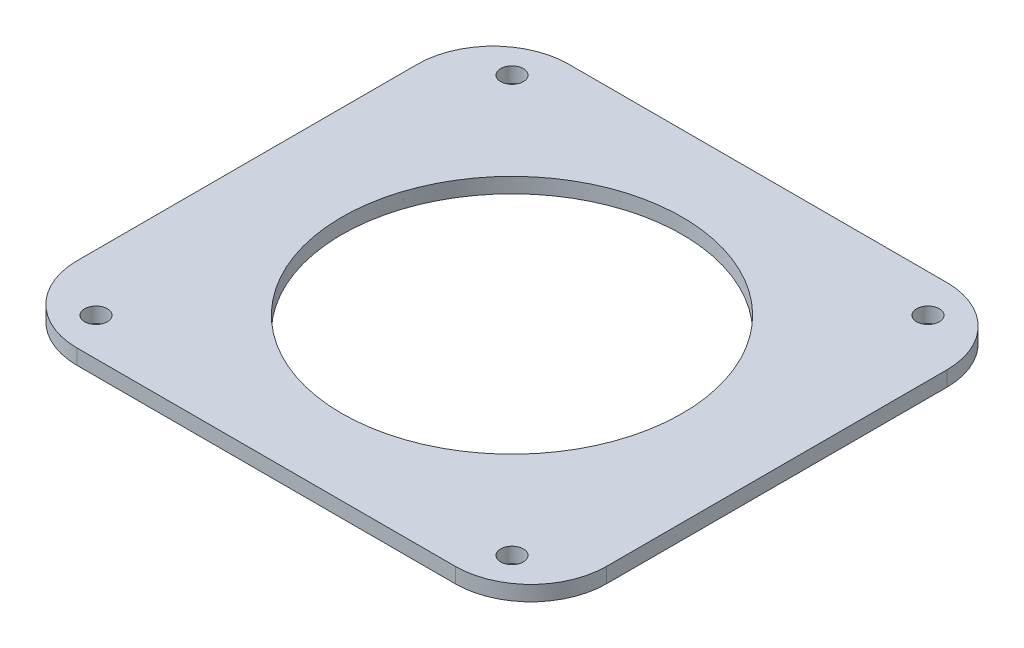
SolidWorks part; units mm, degrees
ref_plane "前视基准面" through (0, 0, 0) normal (0, 0, 1) x (1, 0, 0)
ref_plane "上视基准面" through (0, 0, 0) normal (0, 1, 0) x (1, 0, 0)
ref_plane "右视基准面" through (0, 0, 0) normal (1, 0, 0) x (0, 0, -1)
other "Configuration Table"
sketch "草图1" plane through (0, 0, 0) normal (0, 1, 0) x (1, 0, 0)
  line L1 (-27.5, -27.5) -> (27.5, -27.5)
  line L2 (-27.5, -27.5) -> (-27.5, 27.5)
  line L3 (-27.5, 27.5) -> (27.5, 27.5)
  line L4 (27.5, -27.5) -> (27.5, 27.5)
  line L5 (-27.5, -27.5) -> (27.5, 27.5) construction
  line L6 (-27.5, 27.5) -> (27.5, -27.5) construction
  line L7 (-35, -32.5) -> (35, -32.5)
  line L8 (-35, -32.5) -> (-35, 32.5)
  line L9 (-35, 32.5) -> (35, 32.5)
  line L10 (35, -32.5) -> (35, 32.5)
  line L11 (-35, -32.5) -> (35, 32.5) construction
  line L12 (-35, 32.5) -> (35, -32.5) construction
  circle A0 centre (0, 0) radius 22.5
  circle A1 centre (-27.5, 27.5) radius 1.5
  circle A2 centre (-27.5, -27.5) radius 1.5
  circle A3 centre (27.5, -27.5) radius 1.5
  circle A4 centre (27.5, 27.5) radius 1.5
  point P0 (0, 0)
  point P6 (0, 0)
  dimension "D5" = 45
  dimension "D6" = 3
  dimension "D7" = 3
  dimension "D8" = 3
  dimension "D9" = 3
  dimension "D1" = 55
  dimension "D2" = 55
  dimension "D3" = 70
  dimension "D4" = 65
extrude "凸台-拉伸1" add sketch "草图1" along normal blind 10 contours L7 L10 L9 L8 A4 L4 A3 L1 A2 L2 A1 L3 | A4 L3 A1 L2 A2 L1 A3 L4 A0
fillet "圆角1" radius 10 1 edges at (-35, 5, -32.5)
fillet "圆角2" radius 10 1 edges at (35, 5, -32.5)
fillet "圆角3" radius 10 1 edges at (-35, 5, 32.5)
fillet "圆角4" radius 10 1 edges at (35, 5, 32.5)
sketch "草图2" plane through (0, 10, 0) normal (0, 1, 0) x (1, 0, 0)
  line L1 (-120.4295, 103.3913) -> (41.2036, 103.3913)
  line L2 (-120.4295, 103.3913) -> (-120.4295, -34.994)
  line L3 (-120.4295, -34.994) -> (41.2036, -34.994)
  line L4 (41.2036, 103.3913) -> (41.2036, -34.994)
  line L5 (-120.4295, 103.3913) -> (41.2036, -34.994) construction
  line L6 (-120.4295, -34.994) -> (41.2036, 103.3913) construction
  point P0 (-39.6129, 34.1987)
extrude "切除-拉伸1" cut sketch "草图2" against normal blind 8
